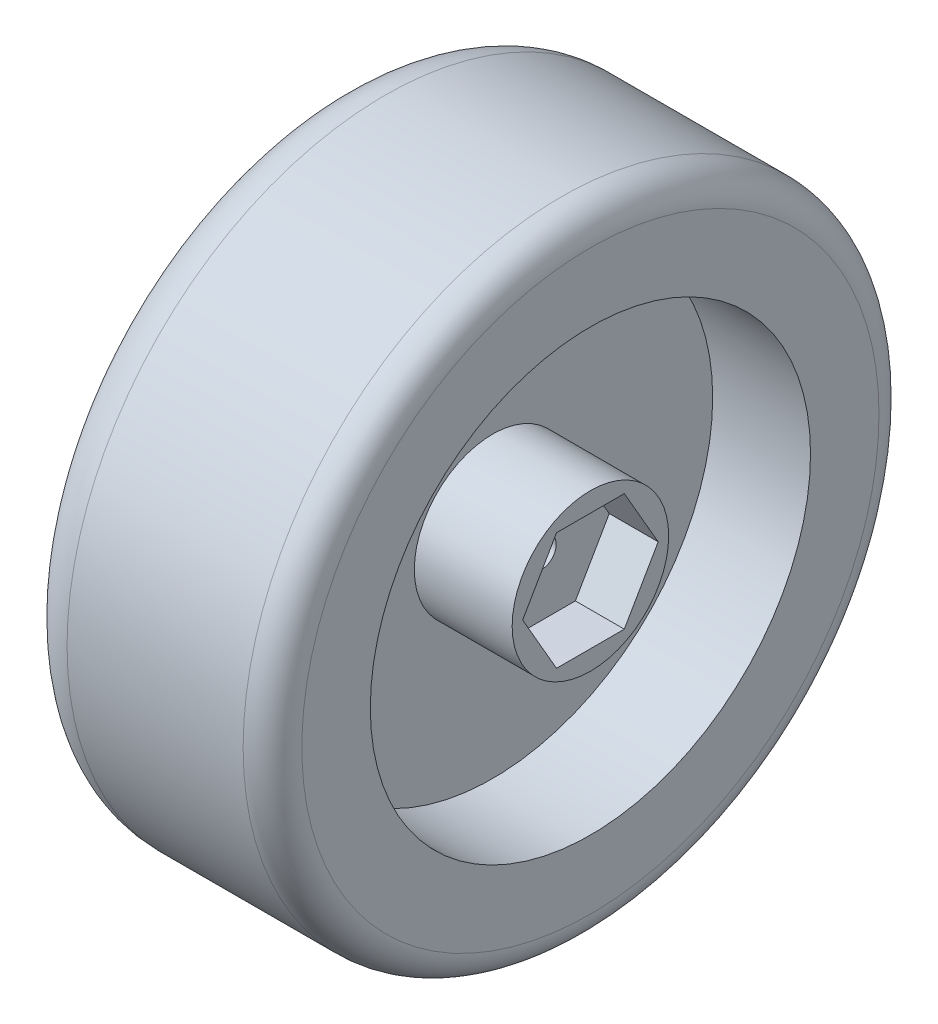
SolidWorks part; units mm, degrees
ref_plane "前视基准面" through (0, 0, 0) normal (0, 0, 1) x (1, 0, 0)
ref_plane "上视基准面" through (0, 0, 0) normal (0, 1, 0) x (1, 0, 0)
ref_plane "右视基准面" through (0, 0, 0) normal (1, 0, 0) x (0, 0, -1)
other "Configuration Table"
ref_plane "基准面1" through (0, 0, 0) normal (0, 0, -1) x (-1, 0, 0)
sketch "草图1" plane through (0, 0, 0) normal (0, 0, -1) x (-1, 0, 0)
  line L0 (-26, 32.5) -> (-26, 0)
  line L1 (-26, 0) -> (0, 0)
  line L2 (0, 0) -> (0, 32.5)
  line L3 (0, 32.5) -> (-26, 32.5)
  line L4 (-26, 0) -> (0, 0) construction
revolve "旋转1" add sketch "草图1" angle 360 about L4
hole_wizard "M39 间隙孔1" positions "草图3" profile "草图2" hole size "M39" standard "ANSI Metric"
sketch "草图3" plane through (26, 0, 0) normal (1, 0, 0) x (0, 0, -1)
  point P0 (0, 0)
sketch "草图2" plane through (26, 0, 0) normal (0, 1, 0) x (0, 0, -1)
  line L0 (0, 0) -> (0, 10)
  line L1 (0, 10) -> (22.5, 10)
  line L2 (22.5, 10) -> (22.5, 0)
  line L5 (22.5, 0) -> (0, 0)
  line L10 (0, 10) -> (-22.5, 10) construction
  line L11 (0, -6.35) -> (0, 107.95) construction
  dimension "孔直径" = 45
  dimension "孔深度" = 10
  dimension "导头角度" = 180
sketch "草图4" plane through (16, 0, 0) normal (1, 0, 0) x (0, 0, -1)
  circle A0 centre (0, 0) radius 8
extrude "凸台-拉伸1" add sketch "草图4" along normal blind 10
sketch "草图5" plane through (26, 0, 0) normal (1, 0, 0) x (0, 0, -1)
  line L0 (3.4641, -6) -> (6.9282, 0)
  line L1 (6.9282, 0) -> (3.4641, 6)
  line L2 (3.4641, 6) -> (-3.4641, 6)
  line L3 (-3.4641, 6) -> (-6.9282, 0)
  line L4 (-6.9282, 0) -> (-3.4641, -6)
  line L5 (-3.4641, -6) -> (3.4641, -6)
extrude "切除-拉伸1" cut sketch "草图5" against normal blind 5
sketch "草图6" plane through (0, 0, 0) normal (1, 0, 0) x (0, 0, -1)
  circle A0 centre (0, 0) radius 1.5
  dimension "D1" = 3
extrude "切除-拉伸2" cut sketch "草图6" along normal through all
fillet "圆角1" radius 5 1 edges at (0, 0, 32.5)
fillet "圆角2" radius 3 1 edges at (26, 0, 32.5)
